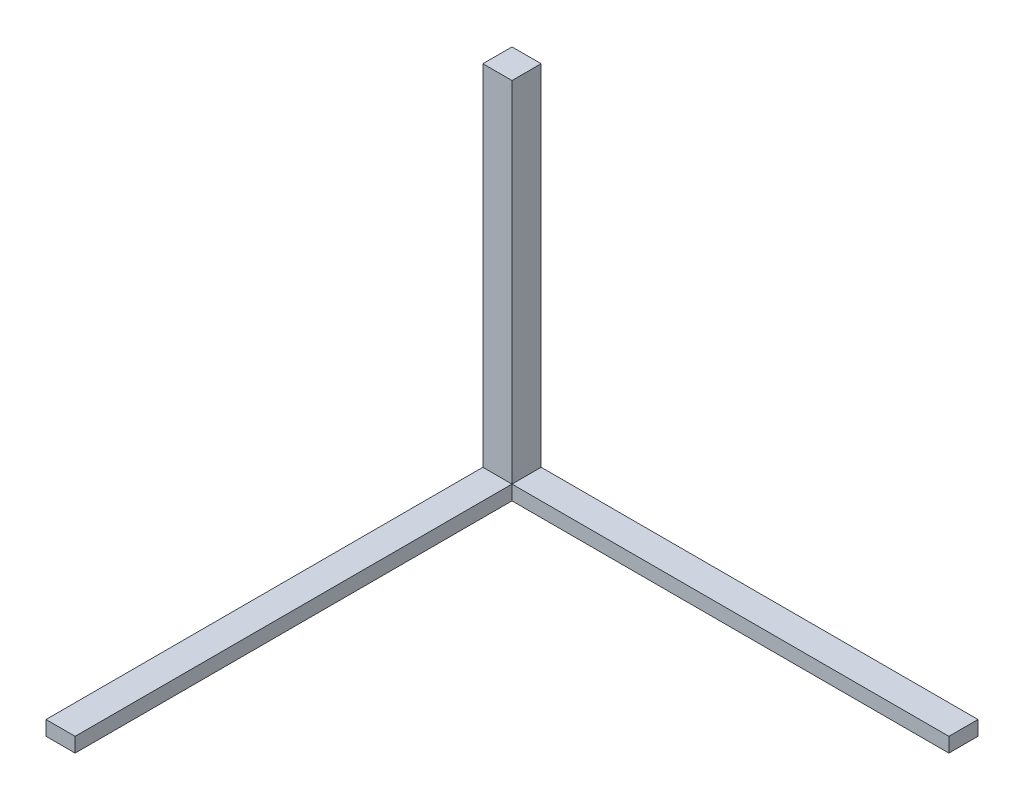
SolidWorks part; units mm, degrees
ref_plane "Front Plane" through (0, 0, 0) normal (0, 0, 1) x (1, 0, 0)
ref_plane "Top Plane" through (0, 0, 0) normal (0, 1, 0) x (1, 0, 0)
ref_plane "Right Plane" through (0, 0, 0) normal (1, 0, 0) x (0, 0, -1)
sketch "Sketch1" plane through (0, 0, 0) normal (0, 1, 0) x (1, 0, 0)
  line L1 (10, -10) -> (-10, -10)
  line L2 (10, -10) -> (10, 10)
  line L3 (10, 10) -> (-10, 10)
  line L4 (-10, -10) -> (-10, 10)
  line L5 (10, -10) -> (-10, 10) construction
  line L6 (10, 10) -> (-10, -10) construction
  point P0 (0, 0)
  dimension "D1" = 20
  dimension "D2" = 20
extrude "Boss-Extrude1" add sketch "Sketch1" along normal blind 250
sketch "Sketch2" plane through (0, 0, 0) normal (0, 1, 0) x (1, 0, 0)
  line L0 (10, -10) -> (10, 10) construction
  line L1 (-10, -10) -> (10, -10)
  line L2 (-10, -10) -> (-10, -310)
  line L3 (-10, -310) -> (10, -310)
  line L4 (10, -10) -> (10, -310)
  line L5 (10, -10) -> (310, -10)
  line L6 (10, -10) -> (10, 10)
  line L7 (10, 10) -> (310, 10)
  line L8 (310, -10) -> (310, 10)
  dimension "D1" = 300
  dimension "D2" = 2
extrude "Boss-Extrude2" add sketch "Sketch2" along normal blind 10 contours L4 L1 L2 L3 | L5 L8 L7 L6
